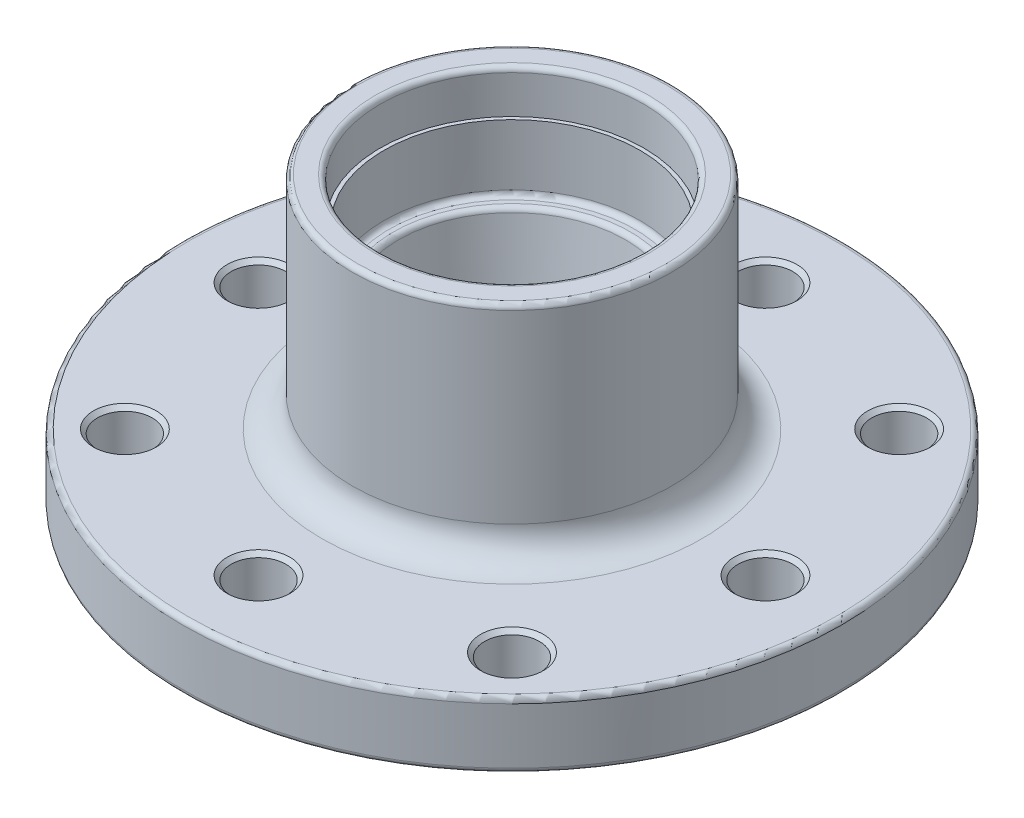
SolidWorks part; units mm, degrees
ref_plane "Plano frontal" through (0, 0, 0) normal (0, 0, 1) x (1, 0, 0)
ref_plane "Plano superior" through (0, 0, 0) normal (0, 1, 0) x (1, 0, 0)
ref_plane "Plano direito" through (0, 0, 0) normal (1, 0, 0) x (0, 0, -1)
sketch "Esboço1" plane through (0, 0, 0) normal (0, 0, 1) x (1, 0, 0)
  line L0 (0, -38.8524) -> (0, 58.5541) construction
  line L1 (26, 58.5541) -> (31.5, 58.5541)
  line L2 (31.5, 58.5541) -> (31.5, 15.0541)
  line L3 (31.5, 15.0541) -> (65, 15.0541)
  line L4 (65, 15.0541) -> (65, 2.0541)
  line L5 (65, 2.0541) -> (27.5, 2.0541)
  line L6 (27.5, 2.0541) -> (27.5, -17.4459)
  line L7 (27.5, -17.4459) -> (20, -17.4459)
  line L8 (20, -17.4459) -> (20, 1.5541)
  line L9 (20, 1.5541) -> (17.5, 1.5541)
  line L10 (17.5, 1.5541) -> (22.5, 37.0541)
  line L11 (22.5, 37.0541) -> (25.25, 37.0541)
  line L12 (25.25, 37.0541) -> (25.25, 50.0541)
  line L13 (25.25, 50.0541) -> (26, 50.0541)
  line L14 (26, 50.0541) -> (26, 58.5541)
  dimension "D1" = 17.5
  dimension "D2" = 20
  dimension "D3" = 27.5
  dimension "D4" = 19.5
  dimension "D5" = 13
  dimension "D6" = 22.5
  dimension "D7" = 25.25
  dimension "D8" = 26
  dimension "D9" = 31.5
  dimension "D10" = 65
  dimension "D11" = 8.5
  dimension "D12" = 21.5
  dimension "D13" = 19
  dimension "D14" = 76
revolve "Revolução1" add sketch "Esboço1" angle 360 about L0
fillet "Filete1" radius 6 1 edges at (0, 15.0541, -31.5)
fillet "Filete2" radius 1 4 edges at (0, 2.0541, -65) (0, 15.0541, -65) (0, 58.5541, -26) (0, 58.5541, -31.5)
fillet "Filete3" radius 1 4 edges at (0, 1.5541, -20) (0, 37.0541, -22.5) (0, 2.0541, -27.5) (0, -17.4459, -27.5)
fillet "Filete4" radius 1 1 edges at (0, 37.0541, -25.25)
sketch "Esboço2" plane through (0, 2.0541, 0) normal (0, -1, 0) x (1, 0, 0)
  circle A0 centre (0, 0) radius 50 construction
  circle A1 centre (0, 50) radius 5.4
  circle A2 centre (50, 0) radius 5.4
  circle A3 centre (0, -50) radius 5.4
  circle A4 centre (-50, 0) radius 5.4
  point P14 (0, 0)
  dimension "D1" = 100
  dimension "D2" = 10.8
  dimension "D3" = 4
extrude "Corte-extrusão1" cut sketch "Esboço2" against normal through all
sketch "Esboço3" plane through (0, 2.0541, 0) normal (0, -1, 0) x (1, 0, 0)
  circle A0 centre (0, 0) radius 54 construction
  circle A2 centre (38.1838, 38.1838) radius 5.4
  circle A4 centre (38.1838, -38.1838) radius 5.4
  circle A6 centre (-38.1838, -38.1838) radius 5.4
  circle A8 centre (-38.1838, 38.1838) radius 5.4
  point P21 (0, 0)
  dimension "D1" = 108
extrude "Corte-extrusão2" cut sketch "Esboço3" against normal through all
chamfer "Chanfro1" distance 0.8 angle 45 16 edges at (0, 15.0541, -44.6) (50, 15.0541, 5.4) (50, 2.0541, -5.4) (38.1838, 15.0541, -32.7838) (38.1838, 2.0541, -43.5838) (0, 2.0541, -55.4) (-38.1838, 15.0541, -32.7838) (-38.1838, 2.0541, -43.5838) (-50, 15.0541, 5.4) (-50, 2.0541, -5.4) (-38.1838, 15.0541, 43.5838) (-38.1838, 2.0541, 32.7838) (0, 15.0541, 55.4) (0, 2.0541, 44.6) (38.1838, 15.0541, 43.5838) (38.1838, 2.0541, 32.7838)
